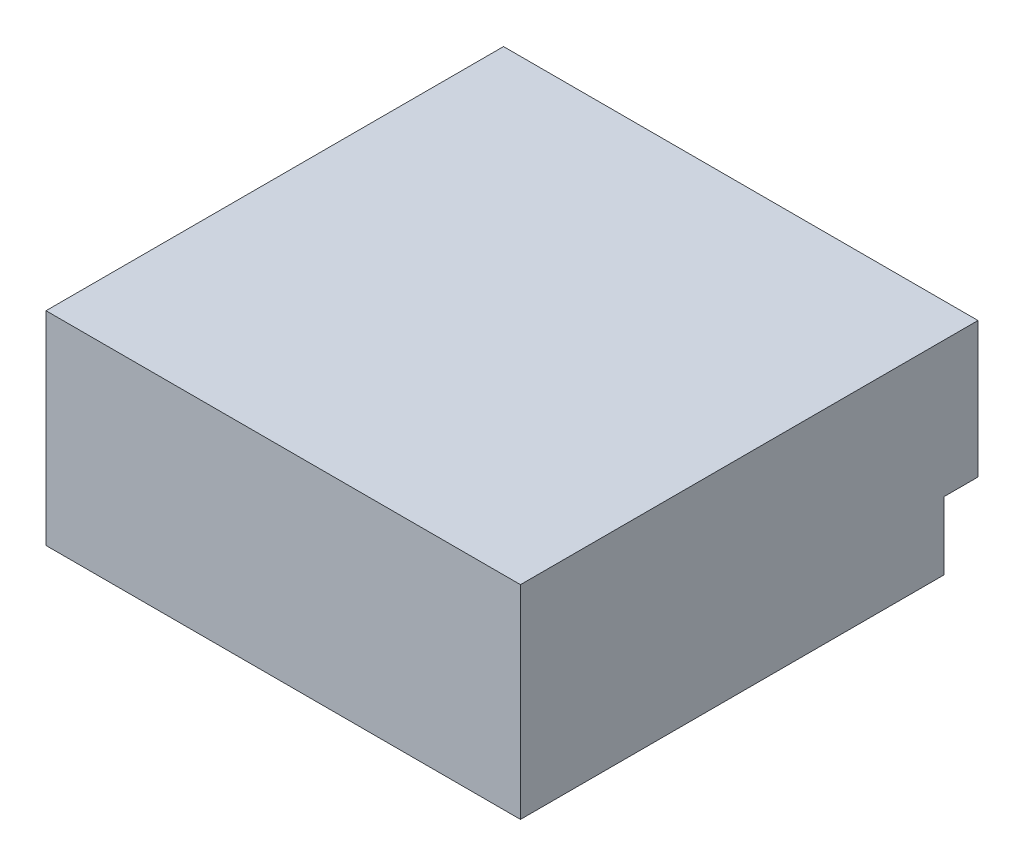
SolidWorks part; units mm, degrees
ref_plane "Front Plane" through (0, 0, 0) normal (0, 0, 1) x (1, 0, 0)
ref_plane "Top Plane" through (0, 0, 0) normal (0, 1, 0) x (1, 0, 0)
ref_plane "Right Plane" through (0, 0, 0) normal (1, 0, 0) x (0, 0, -1)
sketch "Sketch1" plane through (0, 0, 0) normal (0, 0, 1) x (1, 0, 0)
  line L1 (-88.9, 38.1) -> (88.9, 38.1)
  line L2 (-88.9, 38.1) -> (-88.9, -38.1)
  line L3 (-88.9, -38.1) -> (88.9, -38.1)
  line L4 (88.9, 38.1) -> (88.9, -38.1)
  line L5 (-88.9, 38.1) -> (88.9, -38.1) construction
  line L6 (-88.9, -38.1) -> (88.9, 38.1) construction
  point P0 (0, 0)
  dimension "D1" = 177.8
  dimension "D2" = 76.2
extrude "Boss-Extrude1" add sketch "Sketch1" along normal blind 171.45
sketch "Sketch2" plane through (0, 0, 0) normal (0, 0, -1) x (-1, 0, 0)
  line L0 (0, 71.0274) -> (0, -91.693) construction
  line L1 (-88.9, -38.1) -> (-38.1, -38.1)
  line L2 (-88.9, -38.1) -> (-88.9, -12.7)
  line L3 (-88.9, -12.7) -> (-38.1, -12.7)
  line L4 (-38.1, -38.1) -> (-38.1, -12.7)
  line L5 (88.9, -38.1) -> (88.9, -12.7)
  line L6 (88.9, -38.1) -> (38.1, -38.1)
  line L7 (38.1, -38.1) -> (38.1, -12.7)
  line L8 (88.9, -12.7) -> (38.1, -12.7)
  dimension "D1" = 50.8
  dimension "D2" = 25.4
extrude "Cut-Extrude1" cut sketch "Sketch2" against normal blind 12.7
sketch "Sketch3" plane through (0, 0, 12.7) normal (0, 0, -1) x (-1, 0, 0)
  line L0 (-88.9, -38.1) -> (-38.1, -38.1) construction
  line L1 (-88.9, -12.7) -> (-88.9, -38.1) construction
  line L2 (0, 54.1963) -> (0, -66.965) construction
  circle A0 centre (-63.5, -25.4) radius 6.35
  circle A1 centre (63.5, -25.4) radius 6.35
  dimension "D1" = 12.7
  dimension "D2" = 25.4
  dimension "D3" = 12.7
extrude "Boss-Extrude2" add sketch "Sketch3" along normal blind 6.35
